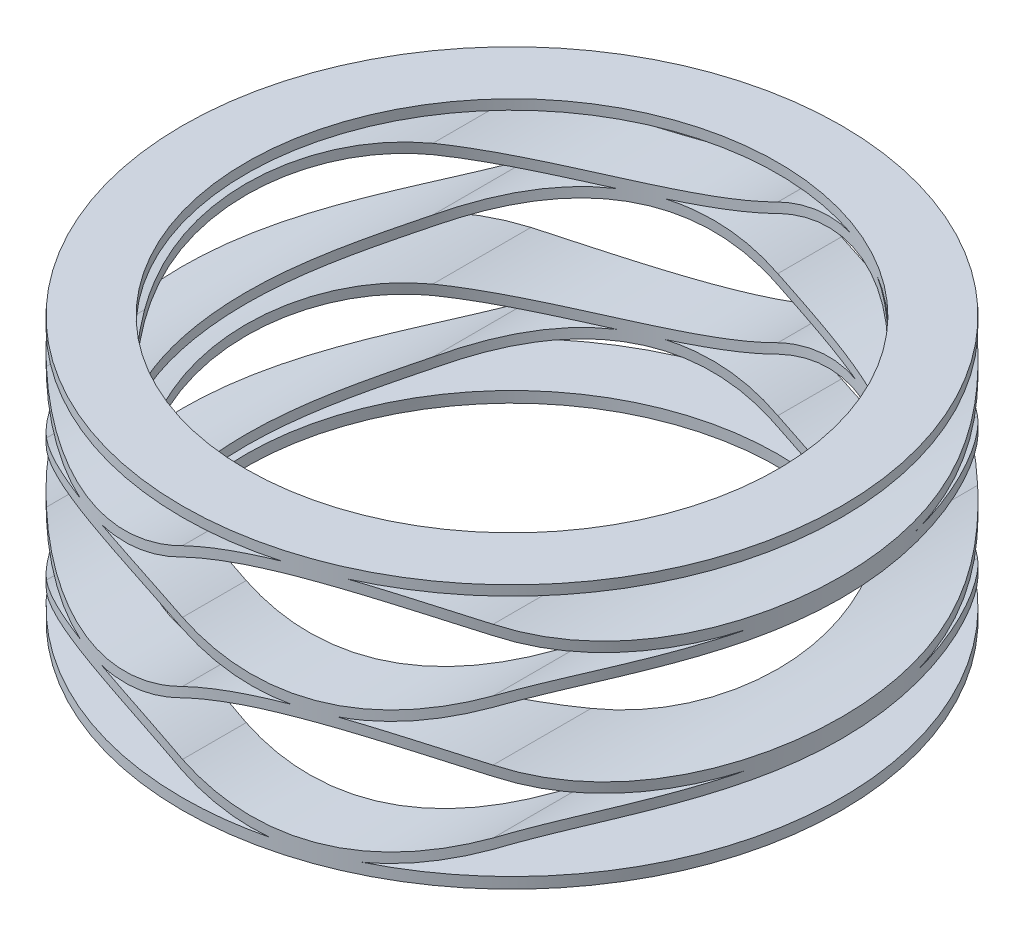
SolidWorks part; units mm, degrees
material "Plain Carbon Steel"
ref_plane "Front Plane" through (0, 0, 0) normal (0, 0, 1) x (1, 0, 0)
ref_plane "Top Plane" through (0, 0, 0) normal (0, 1, 0) x (1, 0, 0)
ref_plane "Right Plane" through (0, 0, 0) normal (1, 0, 0) x (0, 0, -1)
ref_plane "Plane1" through (0, 0, 0) normal (0, 1, 0) x (-1, 0, 0)
sketch "Sketch1" plane through (0, 0, 0) normal (0, 1, 0) x (-1, 0, 0)
  line L0 (15.494, -15.494) -> (15.494, 15.494)
  line L1 (15.494, 15.494) -> (-15.494, 15.494)
  line L2 (-15.494, 15.494) -> (-15.494, -15.494)
  line L3 (-15.494, -15.494) -> (15.494, -15.494)
extrude "Extrude1" add sketch "Sketch1" along normal blind 0.254
ref_plane "Plane2" through (0, 0, 0) normal (0, 0, 1) x (1, 0, 0)
sketch "Sketch2" plane through (0, 0, 0) normal (0, 0, 1) x (1, 0, 0)
  line L0 (10.3293, 0.7937) -> (10.3293, 1.0224)
  line L1 (-10.3293, 1.0224) -> (-10.3293, 0.7937)
  arc A0 (-10.3293, 0.7937) -> (-5.1647, 0.7938) centre (-7.747, 6.1444) ccw
  arc A1 (-5.1647, 0.7938) -> (0, 0.7937) centre (-2.5823, -4.0843) cw
  arc A2 (0, 0.7937) -> (5.1647, 0.7937) centre (2.5823, 6.1444) ccw
  arc A3 (5.1647, 0.7937) -> (10.3293, 0.7937) centre (7.747, -4.0843) cw
  arc A4 (10.3293, 1.0224) -> (5.1647, 1.0224) centre (7.747, -3.8557) ccw
  arc A5 (5.1647, 1.0224) -> (0, 1.0224) centre (2.5823, 6.373) cw
  arc A6 (0, 1.0224) -> (-5.1647, 1.0224) centre (-2.5823, -3.8557) ccw
  arc A7 (-5.1647, 1.0224) -> (-10.3293, 1.0224) centre (-7.747, 6.373) cw
extrude "Extrude2" add sketch "Sketch2" against normal blind 9.4513 and the other way blind 9.4513
ref_plane "Plane3" through (0, 0, 0) normal (0, 0, 1) x (1, 0, 0)
sketch "Sketch3" plane through (0, 0, 0) normal (0, 0, 1) x (1, 0, 0)
  line L0 (-10.3293, 2.4829) -> (-10.3293, 2.2543)
  line L1 (10.3293, 2.2543) -> (10.3293, 2.4829)
  arc A0 (-10.3293, 2.2543) -> (-5.1647, 2.2543) centre (-7.747, -3.0964) cw
  arc A1 (-5.1647, 2.2543) -> (0, 2.2543) centre (-2.5823, 7.3594) ccw
  arc A2 (0, 2.2543) -> (5.1647, 2.2542) centre (2.5823, -3.0964) cw
  arc A3 (5.1647, 2.2542) -> (10.3293, 2.2543) centre (7.747, 7.3594) ccw
  arc A4 (10.3293, 2.4829) -> (5.1647, 2.4828) centre (7.747, 7.588) cw
  arc A5 (5.1647, 2.4828) -> (0, 2.4829) centre (2.5823, -2.8678) ccw
  arc A6 (0, 2.4829) -> (-5.1647, 2.4829) centre (-2.5823, 7.588) cw
  arc A7 (-5.1647, 2.4829) -> (-10.3293, 2.4829) centre (-7.747, -2.8678) ccw
extrude "Extrude3" add sketch "Sketch3" against normal blind 9.2964 and the other way blind 9.2964
ref_plane "Plane4" through (0, 0, 0) normal (0, 0, 1) x (1, 0, 0)
sketch "Sketch4" plane through (0, 0, 0) normal (0, 0, 1) x (1, 0, 0)
  line L0 (10.3293, 3.6385) -> (10.3293, 3.8672)
  line L1 (-10.3293, 3.8672) -> (-10.3293, 3.6385)
  arc A0 (-10.3293, 3.6385) -> (-5.1647, 3.6385) centre (-7.747, 8.9892) ccw
  arc A1 (-5.1647, 3.6385) -> (0, 3.6385) centre (-2.5823, -1.4666) cw
  arc A2 (0, 3.6385) -> (5.1647, 3.6386) centre (2.5823, 8.9892) ccw
  arc A3 (5.1647, 3.6386) -> (10.3293, 3.6385) centre (7.747, -1.4666) cw
  arc A4 (10.3293, 3.8672) -> (5.1647, 3.8672) centre (7.747, -1.238) ccw
  arc A5 (5.1647, 3.8672) -> (0, 3.8672) centre (2.5823, 9.2178) cw
  arc A6 (0, 3.8672) -> (-5.1647, 3.8672) centre (-2.5823, -1.238) ccw
  arc A7 (-5.1647, 3.8672) -> (-10.3293, 3.8672) centre (-7.747, 9.2178) cw
extrude "Extrude4" add sketch "Sketch4" against normal blind 9.2964 and the other way blind 9.2964
ref_plane "Plane5" through (0, 0, 0) normal (0, 0, 1) x (1, 0, 0)
sketch "Sketch5" plane through (0, 0, 0) normal (0, 0, 1) x (1, 0, 0)
  line L0 (-10.3293, 5.3022) -> (-10.3293, 5.0736)
  line L1 (10.3293, 5.0736) -> (10.3293, 5.3022)
  arc A0 (-10.3293, 5.0736) -> (-5.1647, 5.0736) centre (-7.747, -0.277) cw
  arc A1 (-5.1647, 5.0736) -> (0, 5.0736) centre (-2.5823, 10.1788) ccw
  arc A2 (0, 5.0736) -> (5.1647, 5.0736) centre (2.5823, -0.277) cw
  arc A3 (5.1647, 5.0736) -> (10.3293, 5.0736) centre (7.747, 10.1788) ccw
  arc A4 (10.3293, 5.3022) -> (5.1647, 5.3022) centre (7.747, 10.4074) cw
  arc A5 (5.1647, 5.3022) -> (0, 5.3022) centre (2.5823, -0.0484) ccw
  arc A6 (0, 5.3022) -> (-5.1647, 5.3022) centre (-2.5823, 10.4074) cw
  arc A7 (-5.1647, 5.3022) -> (-10.3293, 5.3022) centre (-7.747, -0.0484) ccw
extrude "Extrude5" add sketch "Sketch5" against normal blind 9.2964 and the other way blind 9.2964
ref_plane "Plane6" through (0, 5.8674, 0) normal (0, 1, 0) x (-1, 0, 0)
sketch "Sketch6" plane through (0, 5.8674, 0) normal (0, 1, 0) x (-1, 0, 0)
  line L0 (15.494, -15.494) -> (15.494, 15.494)
  line L1 (15.494, 15.494) -> (-15.494, 15.494)
  line L2 (-15.494, 15.494) -> (-15.494, -15.494)
  line L3 (-15.494, -15.494) -> (15.494, -15.494)
extrude "Extrude6" add sketch "Sketch6" along normal blind 0.2286
ref_plane "Plane7" through (0, 0, 0) normal (0, 1, 0) x (-1, 0, 0)
sketch "Sketch7" plane through (0, 0, 0) normal (0, 1, 0) x (-1, 0, 0)
  line L0 (15.494, -15.494) -> (15.494, 15.494)
  line L1 (15.494, 15.494) -> (-15.494, 15.494)
  line L2 (-15.494, 15.494) -> (-15.494, -15.494)
  line L3 (-15.494, -15.494) -> (15.494, -15.494)
  circle A0 centre (0, 0) radius 7.62
  dimension "D1" = 15.24
extrude "Extrude7" cut sketch "Sketch7" along normal blind 6.096
ref_plane "Plane8" through (0, 0, 0) normal (0, 1, 0) x (-1, 0, 0)
sketch "Sketch8" plane through (0, 0, 0) normal (0, 1, 0) x (-1, 0, 0)
  circle A0 centre (0, 0) radius 6.1468
  circle A1 centre (0, 0) radius 7.62 construction
  dimension "D1" = 1.4732
extrude "Extrude8" cut sketch "Sketch8" along normal blind 6.096
